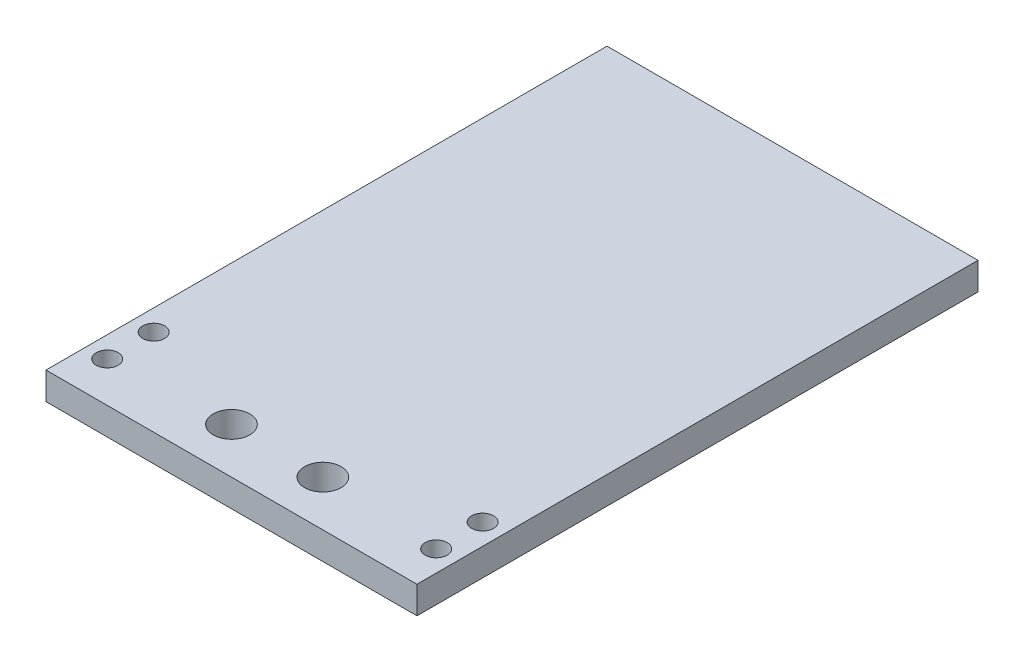
SolidWorks part; units mm, degrees
ref_plane "Спереди" through (0, 0, 0) normal (0, 0, 1) x (1, 0, 0)
ref_plane "Сверху" through (0, 0, 0) normal (0, 1, 0) x (1, 0, 0)
ref_plane "Справа" through (0, 0, 0) normal (1, 0, 0) x (0, 0, -1)
sketch "Эскиз2" plane through (0, 0, 0) normal (0, 1, 0) x (1, 0, 0)
  line L0 (0, 0) -> (0, 18528.664) construction
  line L1 (0, 0) -> (18528.664, 0) construction
  line L2 (-9, -13.15) -> (-9, -10.61) construction
  line L3 (10.15, 15.35) -> (-10.15, 15.35)
  line L4 (10.15, 15.35) -> (10.15, -15.35)
  line L5 (10.15, -15.35) -> (-10.15, -15.35)
  line L6 (-10.15, 15.35) -> (-10.15, -15.35)
  line L7 (10.15, 15.35) -> (-10.15, -15.35) construction
  line L8 (10.15, -15.35) -> (-10.15, 15.35) construction
  circle A0 centre (-9, -13.15) radius 0.6
  circle A1 centre (-9, -10.61) radius 0.6
  circle A2 centre (9, -13.15) radius 0.6
  circle A3 centre (9, -10.61) radius 0.6
  circle A4 centre (-2.5, -12.85) radius 1
  circle A5 centre (2.5, -12.85) radius 1
  point P5 (0, 0)
  dimension "D5" = 1.2
  dimension "D7" = 2
  dimension "D1" = 20.3
  dimension "D2" = 30.7
  dimension "D3" = 18
  dimension "D4" = 2.54
  dimension "D6" = 2.2
  dimension "D8" = 5
  dimension "D9" = 2.5
extrude "Бобышка-Вытянуть1" add sketch "Эскиз2" along normal blind 1.5
